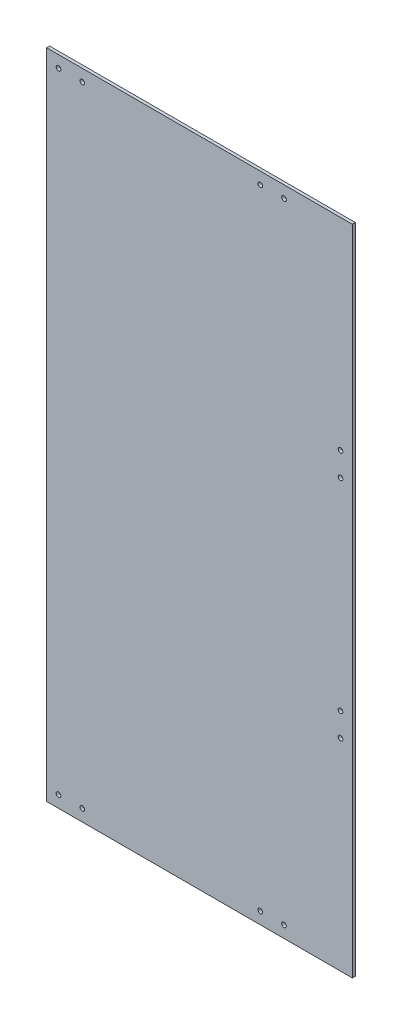
SolidWorks part; units mm, degrees
ref_plane "Front Plane" through (0, 0, 0) normal (1, 0, 0) x (0, 1, 0)
ref_plane "Top Plane" through (0, 0, 0) normal (0, 0, 1) x (0, 1, 0)
ref_plane "Right Plane" through (0, 0, 0) normal (0, 1, 0) x (-1, 0, 0)
sketch "Sketch1" plane through (0, 0, 0) normal (0, 0, 1) x (0, 1, 0)
  line L1 (-349.25, -163.576) -> (349.25, -163.576)
  line L2 (-349.25, -163.576) -> (-349.25, 163.576)
  line L3 (-349.25, 163.576) -> (349.25, 163.576)
  line L4 (349.25, -163.576) -> (349.25, 163.576)
  line L5 (-349.25, -163.576) -> (349.25, 163.576) construction
  line L6 (-349.25, 163.576) -> (349.25, -163.576) construction
  point P0 (0, 0)
  dimension "D1" = 698.5
  dimension "D2" = 327.152
extrude "Boss-Extrude1" add sketch "Sketch1" along normal blind 3.175
sketch "Sketch2" plane through (0, 0, 3.175) normal (0, 0, 1) x (1, 0, 0)
  line L0 (-163.576, 349.25) -> (-163.576, -349.25) construction
  line L1 (-163.576, -349.25) -> (163.576, -349.25) construction
  line L2 (-144.526, -59.6392) -> (-87.376, -59.6392)
  line L3 (-87.376, -54.6608) -> (-144.526, -54.6608)
  circle A0 centre (-144.526, -57.15) radius 2.4892 construction
  circle A1 centre (-87.376, -57.15) radius 2.4892 construction
  arc A2 (-144.526, -59.6392) -> (-144.526, -54.6608) centre (-144.526, -57.15) cw
  arc A3 (-87.376, -59.6392) -> (-87.376, -54.6608) centre (-87.376, -57.15) ccw
  point P0 (-87.376, -57.15)
  point P1 (-144.526, -57.15)
  dimension "D4" = 4.9784
  dimension "D1" = 57.15
  dimension "D2" = 19.05
  dimension "D3" = 292.1
extrude "Cut-Extrude1" [suppressed] cut sketch "Sketch2" against normal through all
sketch "Sketch3" plane through (0, 0, 3.175) normal (0, 0, 1) x (1, 0, 0)
  line L0 (163.576, -349.25) -> (163.576, 349.25) construction
  line L1 (-163.576, -349.25) -> (163.576, -349.25) construction
  point P0 (135.636, -336.55)
  point P3 (135.636, -323.85)
  point P4 (135.636, -311.15)
  point P5 (135.636, -298.45)
  point P6 (135.636, -285.75)
  point P7 (135.636, -273.05)
  point P8 (135.636, -260.35)
  point P9 (135.636, -247.65)
  point P10 (135.636, -234.95)
  point P11 (135.636, -222.25)
  point P12 (135.636, -209.55)
  point P13 (135.636, -196.85)
  point P14 (135.636, -184.15)
  point P15 (135.636, -171.45)
  point P16 (135.636, -158.75)
  point P17 (135.636, -146.05)
  point P18 (135.636, -133.35)
  point P19 (135.636, -120.65)
  point P20 (135.636, -107.95)
  point P21 (135.636, -95.25)
  point P22 (135.636, -82.55)
  point P23 (135.636, -69.85)
  point P24 (135.636, -57.15)
  point P25 (135.636, -44.45)
  dimension "D2" = 27.94
  dimension "D3" = 12.7
  dimension "D4" = 12.7
  dimension "D1" = 24
hole_wizard "#9 (0.196) Diameter Hole1" [suppressed] positions "Sketch3" profile "Sketch4" hole size "#9" standard "ANSI Inch"
sketch "Sketch4" plane through (65.7225, -254, 3.175) normal (1, 0, 0) x (0, -1, 0)
  line L0 (0, 0) -> (0, 3.175)
  line L1 (0, 3.175) -> (2.4892, 3.175)
  line L2 (2.4892, 3.175) -> (2.4892, 0)
  line L5 (2.4892, 0) -> (0, 0)
  line L11 (0, -6.35) -> (0, 107.95) construction
  dimension "Thru Hole Dia." = 4.9784
  dimension "Thru Hole Depth" = 3.175
sketch "Sketch5" plane through (0, 0, 3.175) normal (0, 0, 1) x (1, 0, 0)
  line L0 (-163.576, -349.25) -> (163.576, -349.25) construction
  line L1 (163.576, 349.25) -> (-163.576, 349.25) construction
  line L3 (-163.576, 349.25) -> (-163.576, -349.25) construction
  line L6 (150.876, 107.95) -> (150.876, -107.95) construction
  line L9 (150.876, 133.35) -> (150.876, 349.25) construction
  line L11 (150.876, -133.35) -> (150.876, -349.25) construction
  line L13 (163.576, -349.25) -> (163.576, 349.25) construction
  point P0 (-150.876, 336.55)
  point P1 (-125.476, 336.55)
  point P2 (65.024, 336.55)
  point P3 (90.424, 336.55)
  point P4 (90.424, -336.55)
  point P5 (65.024, -336.55)
  point P6 (-125.476, -336.55)
  point P7 (-150.876, -336.55)
  point P8 (-371.8362, -199.7199)
  point P23 (150.876, 133.35)
  point P25 (150.876, 107.95)
  point P27 (150.876, -107.95)
  point P29 (150.876, -133.35)
  dimension "D1" = 12.7
  dimension "D2" = 12.7
  dimension "D3" = 25.4
  dimension "D4" = 25.4
  dimension "D5" = 190.5
  dimension "D6" = 12.7
  dimension "D7" = 25.4
  dimension "D8" = 25.4
  dimension "D9" = 12.7
hole_wizard "#9 (0.196) Diameter Hole2" positions "Sketch5" profile "Sketch6" hole size "#9" standard "ANSI Inch" end condition through all
sketch "Sketch6" plane through (-150.876, 336.55, 3.175) normal (1, 0, 0) x (0, -1, 0)
  line L0 (0, 0) -> (0, 3.175)
  line L1 (0, 3.175) -> (2.4892, 3.175)
  line L2 (2.4892, 3.175) -> (2.4892, 0)
  line L5 (2.4892, 0) -> (0, 0)
  line L11 (0, -6.35) -> (0, 107.95) construction
  dimension "Thru Hole Dia." = 4.9784
  dimension "Thru Hole Depth" = 3.175
